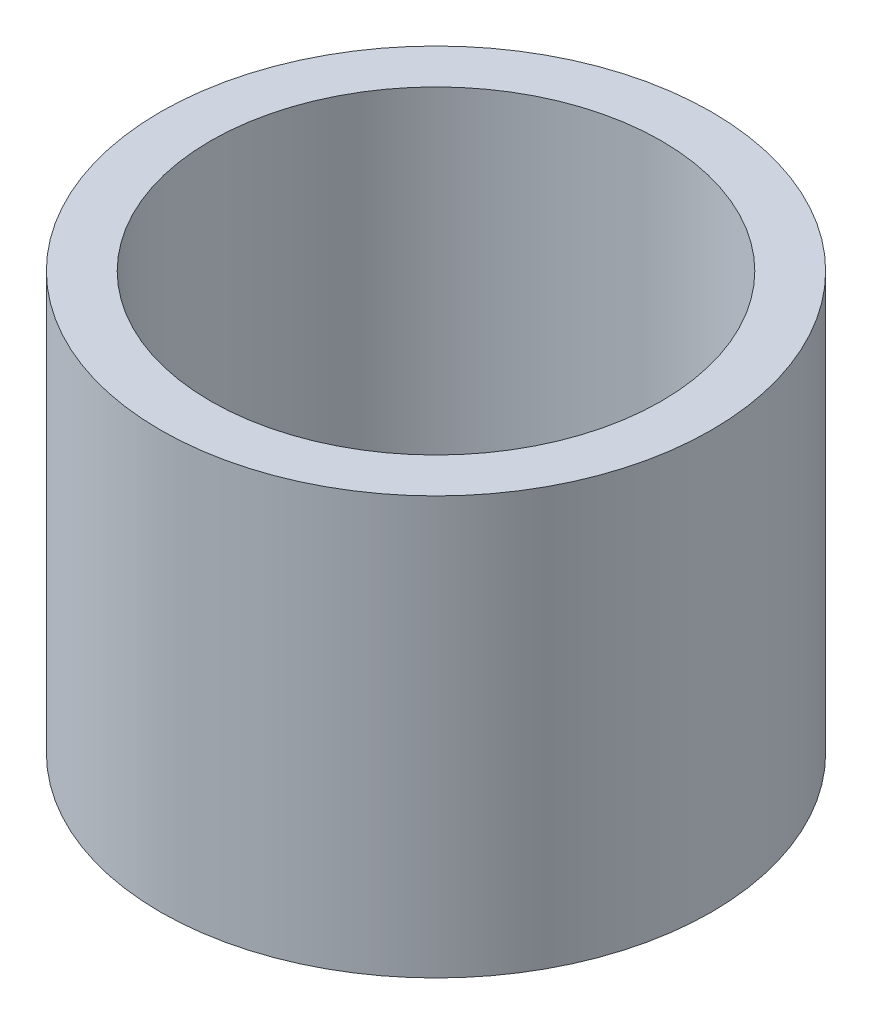
SolidWorks part; units mm, degrees
ref_plane "Front Plane" through (0, 0, 0) normal (0, 0, 1) x (1, 0, 0)
ref_plane "Top Plane" through (0, 0, 0) normal (0, 1, 0) x (1, 0, 0)
ref_plane "Right Plane" through (0, 0, 0) normal (1, 0, 0) x (0, 0, -1)
sketch "Sketch1" plane through (0, 0, 0) normal (0, 1, 0) x (1, 0, 0)
  circle A1 centre (0, 0) radius 13.5
  circle A2 centre (0, 0) radius 16.5
  dimension "D1" = 27
  dimension "D2" = 3
extrude "Boss-Extrude1" add sketch "Sketch1" along normal blind 25
